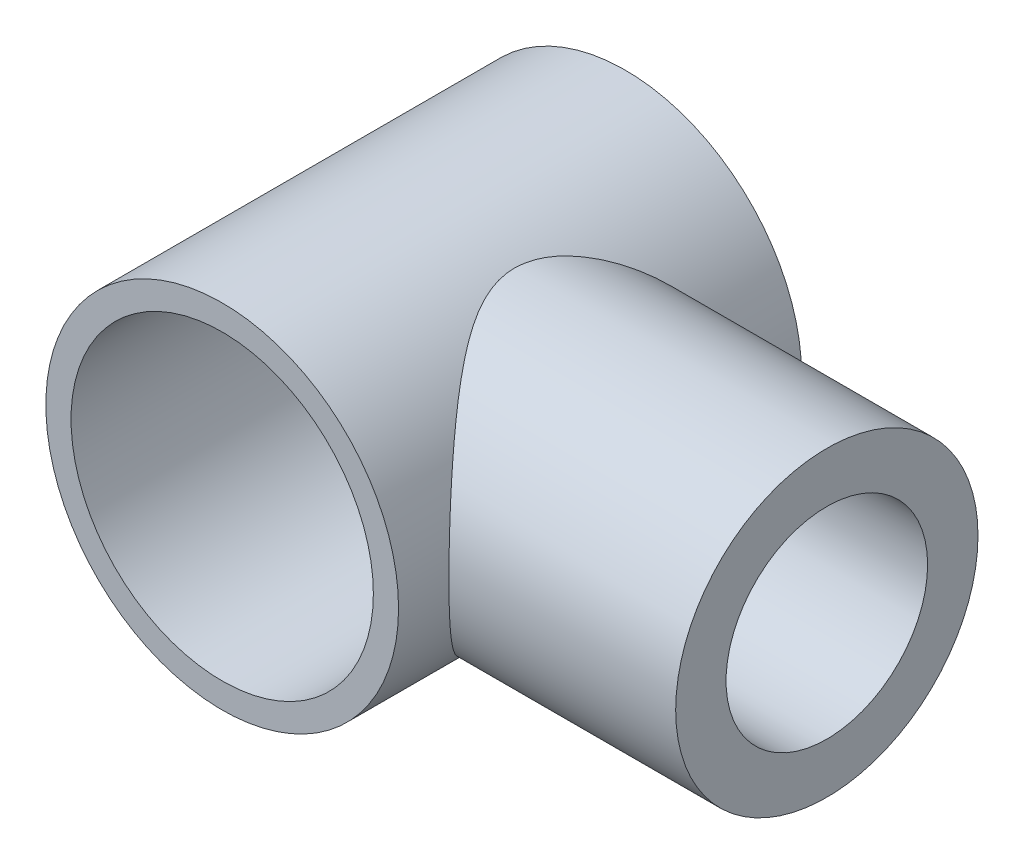
SolidWorks part; units mm, degrees
ref_plane "Front Plane" through (0, 0, 0) normal (1, 0, 0) x (0, 1, 0)
ref_plane "Top Plane" through (0, 0, 0) normal (0, 0, 1) x (0, 1, 0)
ref_plane "Right Plane" through (0, 0, 0) normal (0, 1, 0) x (-1, 0, 0)
sketch "Sketch1" plane through (0, 0, 0) normal (1, 0, 0) x (0, 1, 0)
  circle A0 centre (0, 0) radius 19.05
  circle A1 centre (0, 0) radius 12.7
  dimension "D1" = 38.1
  dimension "D2" = 25.4
extrude "Boss-Extrude1" add sketch "Sketch1" along normal blind 50.8
sketch "Sketch2" plane through (0, 0, 0) normal (0, 0, 1) x (0, 1, 0)
  line L0 (0, 59.3872) -> (0, -90.5042) construction
  circle A0 centre (0, 0) radius 22.225
  circle A1 centre (0, 0) radius 19.05
  dimension "D1" = 38.1
  dimension "D2" = 44.45
extrude "Boss-Extrude2" add sketch "Sketch2" along normal mid plane 50.8
sketch "Sketch3" plane through (0, 0, 25.4) normal (0, 0, 1) x (1, 0, 0)
  circle A0 centre (0, 0) radius 19.05
extrude "Cut-Extrude1" cut sketch "Sketch3" against normal blind 50.8
sketch "Sketch4" plane through (50.8, 0, 0) normal (1, 0, 0) x (0, 1, 0)
  circle A0 centre (0, 0) radius 12.7
extrude "Cut-Extrude2" cut sketch "Sketch4" against normal blind 50.8
